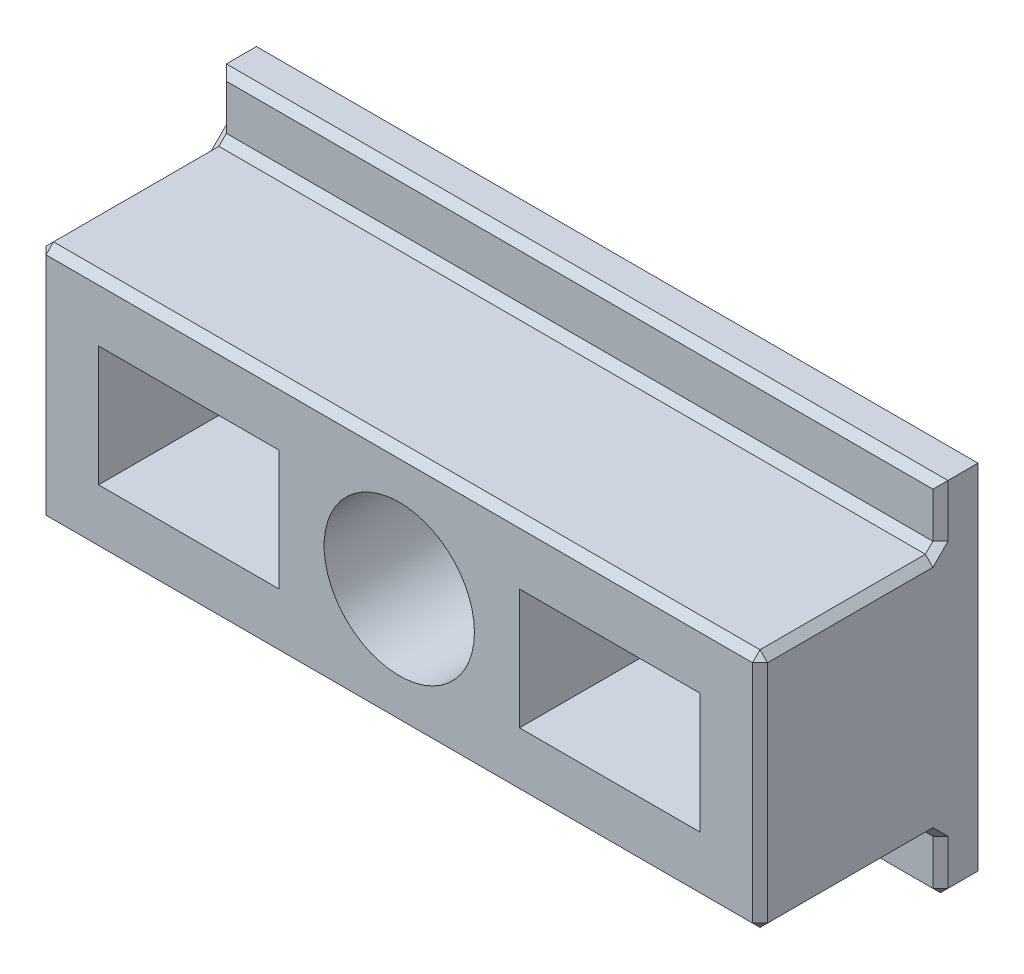
SolidWorks part; units mm, degrees
ref_plane "Front Plane" through (0, 0, 0) normal (0, 0, 1) x (1, 0, 0)
ref_plane "Top Plane" through (0, 0, 0) normal (0, 1, 0) x (1, 0, 0)
ref_plane "Right Plane" through (0, 0, 0) normal (1, 0, 0) x (0, 0, -1)
sketch "Sketch1" plane through (0, 0, 0) normal (0, 0, 1) x (1, 0, 0)
  line L1 (12, -4) -> (-12, -4)
  line L2 (12, -4) -> (12, 4)
  line L3 (12, 4) -> (-12, 4)
  line L4 (-12, -4) -> (-12, 4)
  line L5 (12, -4) -> (-12, 4) construction
  line L6 (12, 4) -> (-12, -4) construction
  point P0 (0, 0)
  dimension "D1" = 12
  dimension "D2" = 4
extrude "Boss-Extrude1" add sketch "Sketch1" against normal blind 6
sketch "Sketch2" plane through (0, 0, -6) normal (0, 0, -1) x (-1, 0, 0)
  line L0 (-12, -4) -> (-12, 4) construction
  line L1 (12, -6) -> (-12, -6)
  line L2 (12, -6) -> (12, 6)
  line L3 (12, 6) -> (-12, 6)
  line L4 (-12, -6) -> (-12, 6)
  line L5 (12, -6) -> (-12, 6) construction
  line L6 (12, 6) -> (-12, -6) construction
  line L7 (-12, 4) -> (12, 4) construction
  point P0 (0, 0)
  dimension "D1" = 2
extrude "Boss-Extrude2" add sketch "Sketch2" along normal blind 1.5
sketch "Sketch3" plane through (0, 0, 0) normal (0, 0, 1) x (1, 0, 0)
  line L0 (0, 0) -> (0, 4) construction
  line L1 (-10, 2) -> (-4, 2)
  line L2 (-10, 2) -> (-10, -2)
  line L3 (-10, -2) -> (-4, -2)
  line L4 (-4, 2) -> (-4, -2)
  line L5 (12, 4) -> (-12, 4) construction
  line L6 (-12, 4) -> (-12, -4) construction
  line L7 (10, -2) -> (4, -2)
  line L8 (4, 2) -> (4, -2)
  line L9 (10, 2) -> (4, 2)
  line L10 (10, 2) -> (10, -2)
  circle A0 centre (0, 0) radius 2.5
  point P12 (-4, 0)
  dimension "D1" = 5
  dimension "D2" = 4
  dimension "D3" = 2
  dimension "D4" = 2
extrude "Cut-Extrude1" cut sketch "Sketch3" against normal through all
chamfer "Chamfer1" distance 0.25 angle 45 21 edges at (0, 6, -6) (-12, -5, -6) (-12, 5, -6) (12, 5, -6) (-12, 0, 0) (-12, 0, -7.5) (0, -6, -7.5) (-12, -4, -3) (0, -4, 0) (0, -4, -6) (0, -6, -6) (0, 6, -7.5) (12, 0, -7.5) (12, -6, -6.75) (12, -5, -6) (12, -4, -3) (12, 0, 0) (-12, 4, -3) (0, 4, -6) (12, 4, -3) (0, 4, 0)
